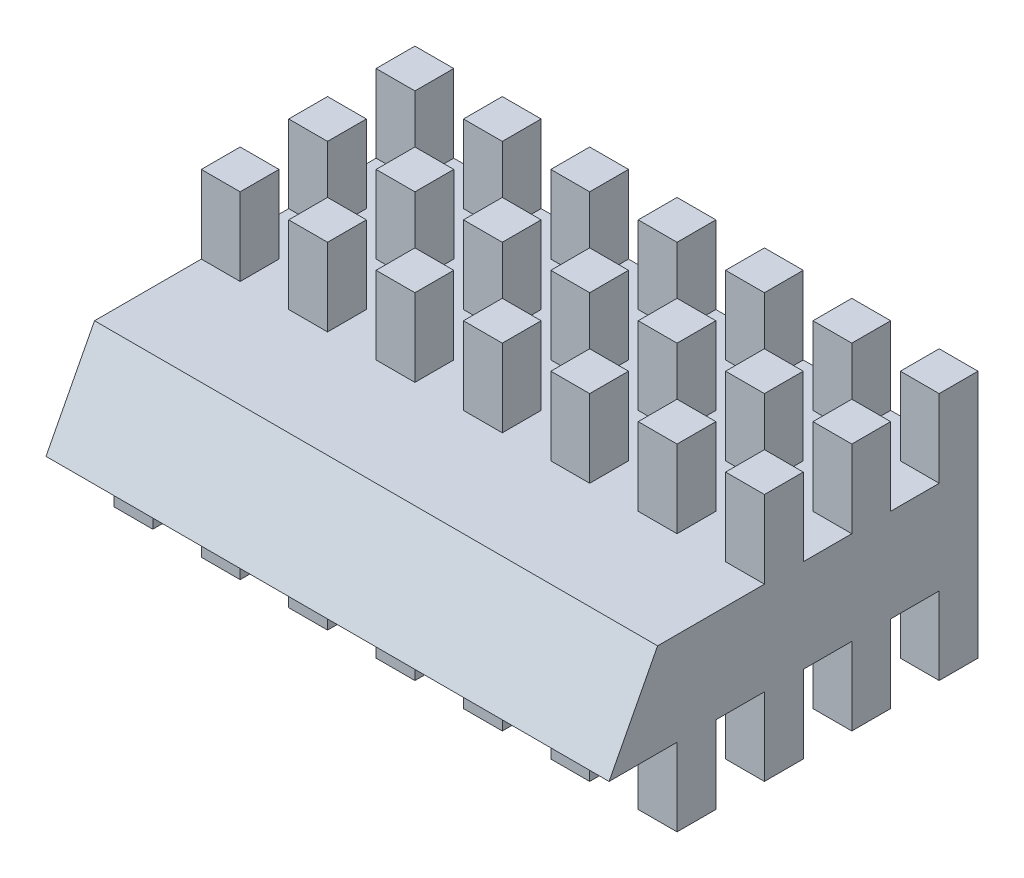
SolidWorks part; units mm, degrees
ref_plane "Front Plane" through (0, 0, 0) normal (0, 0, 1) x (1, 0, 0)
ref_plane "Top Plane" through (0, 0, 0) normal (0, 1, 0) x (1, 0, 0)
ref_plane "Right Plane" through (0, 0, 0) normal (1, 0, 0) x (0, 0, -1)
sketch "Sketch1" plane through (0, 0, 0) normal (0, 1, 0) x (1, 0, 0)
  line L1 (0, 0) -> (18.415, 0)
  line L2 (0, 0) -> (0, 17.78)
  line L3 (0, 17.78) -> (18.415, 17.78)
  line L4 (18.415, 0) -> (18.415, 17.78)
  dimension "D1" = 18.415
  dimension "D2" = 17.78
extrude "Boss-Extrude1" add sketch "Sketch1" along normal blind 1.524
sketch "Sketch2" plane through (0, 1.524, 0) normal (0, 1, 0) x (1, 0, 0)
  line L0 (2.8575, 17.78) -> (4.1275, 17.78)
  line L1 (0, 17.78) -> (1.27, 17.78)
  line L2 (0, 17.78) -> (0, 16.51)
  line L3 (0, 16.51) -> (1.27, 16.51)
  line L4 (1.27, 17.78) -> (1.27, 16.51)
  line L5 (2.8575, 17.78) -> (2.8575, 16.51)
  line L6 (2.8575, 16.51) -> (4.1275, 16.51)
  line L7 (4.1275, 17.78) -> (4.1275, 16.51)
  line L8 (5.715, 17.78) -> (6.985, 17.78)
  line L9 (5.715, 17.78) -> (5.715, 16.51)
  line L10 (5.715, 16.51) -> (6.985, 16.51)
  line L11 (6.985, 17.78) -> (6.985, 16.51)
  line L12 (8.5725, 17.78) -> (9.8425, 17.78)
  line L13 (8.5725, 17.78) -> (8.5725, 16.51)
  line L14 (8.5725, 16.51) -> (9.8425, 16.51)
  line L15 (9.8425, 17.78) -> (9.8425, 16.51)
  line L16 (11.43, 17.78) -> (12.7, 17.78)
  line L17 (11.43, 17.78) -> (11.43, 16.51)
  line L18 (11.43, 16.51) -> (12.7, 16.51)
  line L19 (12.7, 17.78) -> (12.7, 16.51)
  line L20 (14.2875, 17.78) -> (15.5575, 17.78)
  line L21 (14.2875, 17.78) -> (14.2875, 16.51)
  line L22 (14.2875, 16.51) -> (15.5575, 16.51)
  line L23 (15.5575, 17.78) -> (15.5575, 16.51)
  line L24 (17.145, 17.78) -> (18.415, 17.78)
  line L25 (17.145, 17.78) -> (17.145, 16.51)
  line L26 (17.145, 16.51) -> (18.415, 16.51)
  line L27 (18.415, 17.78) -> (18.415, 16.51)
  line L28 (2.8575, 14.9225) -> (4.1275, 14.9225)
  line L29 (2.8575, 14.9225) -> (2.8575, 13.6525)
  line L30 (2.8575, 13.6525) -> (4.1275, 13.6525)
  line L31 (4.1275, 14.9225) -> (4.1275, 13.6525)
  line L32 (5.715, 14.9225) -> (6.985, 14.9225)
  line L33 (5.715, 14.9225) -> (5.715, 13.6525)
  line L34 (5.715, 13.6525) -> (6.985, 13.6525)
  line L35 (6.985, 14.9225) -> (6.985, 13.6525)
  line L36 (8.5725, 14.9225) -> (9.8425, 14.9225)
  line L37 (8.5725, 14.9225) -> (8.5725, 13.6525)
  line L38 (8.5725, 13.6525) -> (9.8425, 13.6525)
  line L39 (9.8425, 14.9225) -> (9.8425, 13.6525)
  line L40 (11.43, 14.9225) -> (12.7, 14.9225)
  line L41 (11.43, 14.9225) -> (11.43, 13.6525)
  line L42 (11.43, 13.6525) -> (12.7, 13.6525)
  line L43 (12.7, 14.9225) -> (12.7, 13.6525)
  line L44 (14.2875, 14.9225) -> (15.5575, 14.9225)
  line L45 (14.2875, 14.9225) -> (14.2875, 13.6525)
  line L46 (14.2875, 13.6525) -> (15.5575, 13.6525)
  line L47 (15.5575, 14.9225) -> (15.5575, 13.6525)
  line L48 (17.145, 14.9225) -> (18.415, 14.9225)
  line L49 (17.145, 14.9225) -> (17.145, 13.6525)
  line L50 (17.145, 13.6525) -> (18.415, 13.6525)
  line L51 (18.415, 14.9225) -> (18.415, 13.6525)
  line L52 (2.8575, 12.065) -> (4.1275, 12.065)
  line L53 (2.8575, 12.065) -> (2.8575, 10.795)
  line L54 (2.8575, 10.795) -> (4.1275, 10.795)
  line L55 (4.1275, 12.065) -> (4.1275, 10.795)
  line L56 (5.715, 12.065) -> (6.985, 12.065)
  line L57 (5.715, 12.065) -> (5.715, 10.795)
  line L58 (5.715, 10.795) -> (6.985, 10.795)
  line L59 (6.985, 12.065) -> (6.985, 10.795)
  line L60 (8.5725, 12.065) -> (9.8425, 12.065)
  line L61 (8.5725, 12.065) -> (8.5725, 10.795)
  line L62 (8.5725, 10.795) -> (9.8425, 10.795)
  line L63 (9.8425, 12.065) -> (9.8425, 10.795)
  line L64 (11.43, 12.065) -> (12.7, 12.065)
  line L65 (11.43, 12.065) -> (11.43, 10.795)
  line L66 (11.43, 10.795) -> (12.7, 10.795)
  line L67 (12.7, 12.065) -> (12.7, 10.795)
  line L68 (14.2875, 12.065) -> (15.5575, 12.065)
  line L69 (14.2875, 12.065) -> (14.2875, 10.795)
  line L70 (14.2875, 10.795) -> (15.5575, 10.795)
  line L71 (15.5575, 12.065) -> (15.5575, 10.795)
  line L72 (17.145, 12.065) -> (18.415, 12.065)
  line L73 (17.145, 12.065) -> (17.145, 10.795)
  line L74 (17.145, 10.795) -> (18.415, 10.795)
  line L75 (18.415, 12.065) -> (18.415, 10.795)
  line L76 (2.8575, 9.2075) -> (4.1275, 9.2075)
  line L77 (2.8575, 9.2075) -> (2.8575, 7.9375)
  line L78 (2.8575, 7.9375) -> (4.1275, 7.9375)
  line L79 (4.1275, 9.2075) -> (4.1275, 7.9375)
  line L80 (5.715, 9.2075) -> (6.985, 9.2075)
  line L81 (5.715, 9.2075) -> (5.715, 7.9375)
  line L82 (5.715, 7.9375) -> (6.985, 7.9375)
  line L83 (6.985, 9.2075) -> (6.985, 7.9375)
  line L84 (8.5725, 9.2075) -> (9.8425, 9.2075)
  line L85 (8.5725, 9.2075) -> (8.5725, 7.9375)
  line L86 (8.5725, 7.9375) -> (9.8425, 7.9375)
  line L87 (9.8425, 9.2075) -> (9.8425, 7.9375)
  line L88 (11.43, 9.2075) -> (12.7, 9.2075)
  line L89 (11.43, 9.2075) -> (11.43, 7.9375)
  line L90 (11.43, 7.9375) -> (12.7, 7.9375)
  line L91 (12.7, 9.2075) -> (12.7, 7.9375)
  line L92 (14.2875, 9.2075) -> (15.5575, 9.2075)
  line L93 (14.2875, 9.2075) -> (14.2875, 7.9375)
  line L94 (14.2875, 7.9375) -> (15.5575, 7.9375)
  line L95 (15.5575, 9.2075) -> (15.5575, 7.9375)
  line L96 (17.145, 9.2075) -> (18.415, 9.2075)
  line L97 (17.145, 9.2075) -> (17.145, 7.9375)
  line L98 (17.145, 7.9375) -> (18.415, 7.9375)
  line L99 (18.415, 9.2075) -> (18.415, 7.9375)
  line L100 (2.8575, 6.35) -> (4.1275, 6.35)
  line L101 (2.8575, 6.35) -> (2.8575, 5.08)
  line L102 (2.8575, 5.08) -> (4.1275, 5.08)
  line L103 (4.1275, 6.35) -> (4.1275, 5.08)
  line L104 (5.715, 6.35) -> (6.985, 6.35)
  line L105 (5.715, 6.35) -> (5.715, 5.08)
  line L106 (5.715, 5.08) -> (6.985, 5.08)
  line L107 (6.985, 6.35) -> (6.985, 5.08)
  line L108 (8.5725, 6.35) -> (9.8425, 6.35)
  line L109 (8.5725, 6.35) -> (8.5725, 5.08)
  line L110 (8.5725, 5.08) -> (9.8425, 5.08)
  line L111 (9.8425, 6.35) -> (9.8425, 5.08)
  line L112 (11.43, 6.35) -> (12.7, 6.35)
  line L113 (11.43, 6.35) -> (11.43, 5.08)
  line L114 (11.43, 5.08) -> (12.7, 5.08)
  line L115 (12.7, 6.35) -> (12.7, 5.08)
  line L116 (14.2875, 6.35) -> (15.5575, 6.35)
  line L117 (14.2875, 6.35) -> (14.2875, 5.08)
  line L118 (14.2875, 5.08) -> (15.5575, 5.08)
  line L119 (15.5575, 6.35) -> (15.5575, 5.08)
  line L120 (17.145, 6.35) -> (18.415, 6.35)
  line L121 (17.145, 6.35) -> (17.145, 5.08)
  line L122 (17.145, 5.08) -> (18.415, 5.08)
  line L123 (18.415, 6.35) -> (18.415, 5.08)
  line L124 (2.8575, 3.4925) -> (4.1275, 3.4925)
  line L125 (2.8575, 3.4925) -> (2.8575, 2.2225)
  line L126 (2.8575, 2.2225) -> (4.1275, 2.2225)
  line L127 (4.1275, 3.4925) -> (4.1275, 2.2225)
  line L128 (5.715, 3.4925) -> (6.985, 3.4925)
  line L129 (5.715, 3.4925) -> (5.715, 2.2225)
  line L130 (5.715, 2.2225) -> (6.985, 2.2225)
  line L131 (6.985, 3.4925) -> (6.985, 2.2225)
  line L132 (8.5725, 3.4925) -> (9.8425, 3.4925)
  line L133 (8.5725, 3.4925) -> (8.5725, 2.2225)
  line L134 (8.5725, 2.2225) -> (9.8425, 2.2225)
  line L135 (9.8425, 3.4925) -> (9.8425, 2.2225)
  line L136 (11.43, 3.4925) -> (12.7, 3.4925)
  line L137 (11.43, 3.4925) -> (11.43, 2.2225)
  line L138 (11.43, 2.2225) -> (12.7, 2.2225)
  line L139 (12.7, 3.4925) -> (12.7, 2.2225)
  line L140 (14.2875, 3.4925) -> (15.5575, 3.4925)
  line L141 (14.2875, 3.4925) -> (14.2875, 2.2225)
  line L142 (14.2875, 2.2225) -> (15.5575, 2.2225)
  line L143 (15.5575, 3.4925) -> (15.5575, 2.2225)
  line L144 (17.145, 3.4925) -> (18.415, 3.4925)
  line L145 (17.145, 3.4925) -> (17.145, 2.2225)
  line L146 (17.145, 2.2225) -> (18.415, 2.2225)
  line L147 (18.415, 3.4925) -> (18.415, 2.2225)
  line L148 (0, 14.9225) -> (1.27, 14.9225)
  line L149 (0, 14.9225) -> (0, 13.6525)
  line L150 (0, 13.6525) -> (1.27, 13.6525)
  line L151 (1.27, 14.9225) -> (1.27, 13.6525)
  line L152 (0, 12.065) -> (1.27, 12.065)
  line L153 (0, 12.065) -> (0, 10.795)
  line L154 (0, 10.795) -> (1.27, 10.795)
  line L155 (1.27, 12.065) -> (1.27, 10.795)
  line L156 (0, 9.2075) -> (1.27, 9.2075)
  line L157 (0, 9.2075) -> (0, 7.9375)
  line L158 (0, 7.9375) -> (1.27, 7.9375)
  line L159 (1.27, 9.2075) -> (1.27, 7.9375)
  line L160 (0, 6.35) -> (1.27, 6.35)
  line L161 (0, 6.35) -> (0, 5.08)
  line L162 (0, 5.08) -> (1.27, 5.08)
  line L163 (1.27, 6.35) -> (1.27, 5.08)
  line L164 (0, 3.4925) -> (1.27, 3.4925)
  line L165 (0, 3.4925) -> (0, 2.2225)
  line L166 (0, 2.2225) -> (1.27, 2.2225)
  line L167 (1.27, 3.4925) -> (1.27, 2.2225)
  dimension "D1" = 1.27
  dimension "D2" = 1.27
  dimension "D3" = 7
  dimension "D4" = 6
extrude "Boss-Extrude3" add sketch "Sketch2" along normal blind 2.54
mirror "Mirror1" about plane through (0, 0, 0) normal (0, -1, 0) of "Boss-Extrude1", "Boss-Extrude3"
sketch "Sketch3" plane through (18.415, 0, 0) normal (1, 0, 0) x (0, 0, -1)
  line L0 (0, -1.524) -> (1.5867, 1.524)
  line L1 (0, 1.524) -> (2.2225, 1.524) construction
  line L2 (1.5867, 1.524) -> (0, 1.524)
  line L3 (0, 1.524) -> (0, -1.524)
  line L5 (2.2225, 1.524) -> (3.4925, 1.524)
  line L6 (2.2225, 1.524) -> (2.2225, 4.064)
  line L7 (2.2225, 4.064) -> (3.4925, 4.064)
  line L8 (3.4925, 1.524) -> (3.4925, 4.064)
  dimension "D1" = 27.5
extrude "Cut-Extrude1" cut sketch "Sketch3" against normal through all
sketch "Sketch4" plane through (18.415, 0, 0) normal (1, 0, 0) x (0, 0, -1)
  line L1 (12.065, 4.064) -> (17.78, 4.064)
  line L2 (12.065, 4.064) -> (12.065, -4.064)
  line L3 (12.065, -4.064) -> (17.78, -4.064)
  line L4 (17.78, 4.064) -> (17.78, -4.064)
extrude "Cut-Extrude2" cut sketch "Sketch4" against normal through all
